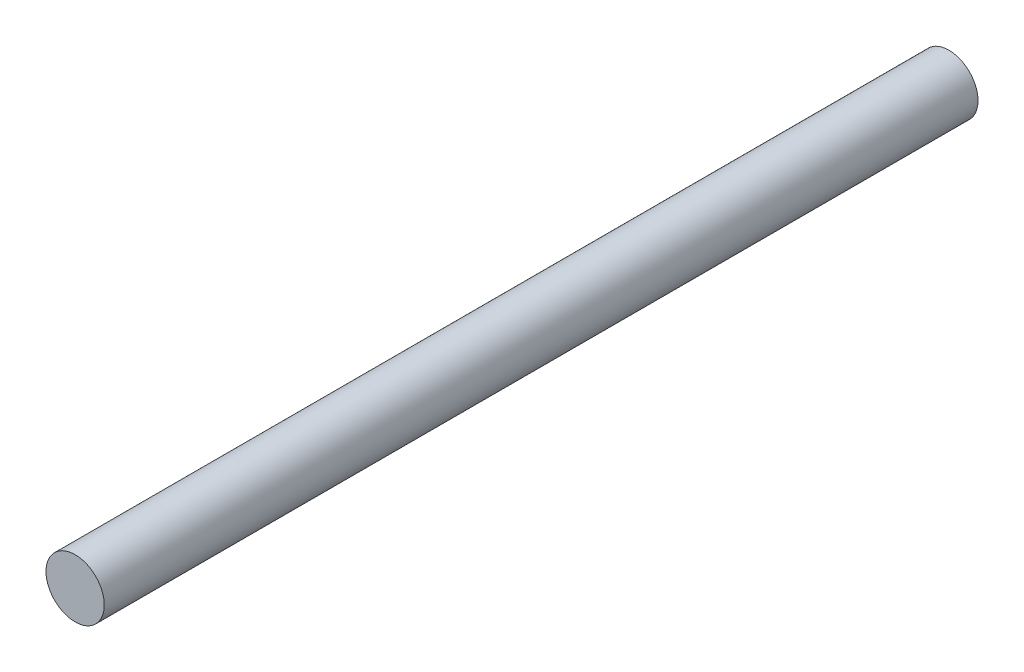
SolidWorks part; units mm, degrees
ref_plane "Front Plane" through (0, 0, 0) normal (0, 0, 1) x (1, 0, 0)
ref_plane "Top Plane" through (0, 0, 0) normal (0, 1, 0) x (1, 0, 0)
ref_plane "Right Plane" through (0, 0, 0) normal (1, 0, 0) x (0, 0, -1)
sketch "Sketch1" plane through (0, 0, 0) normal (0, 0, 1) x (1, 0, 0)
  circle A0 centre (-1.0011, 0.5641) radius 1.5
  dimension "D1" = 3
extrude "Boss-Extrude1" add sketch "Sketch1" along normal blind 45
